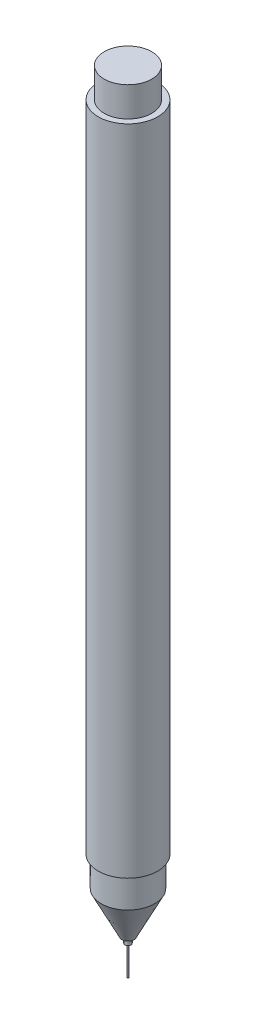
SolidWorks part; units mm, degrees
ref_plane "Front Plane" through (0, 0, 0) normal (0, 0, 1) x (1, 0, 0)
ref_plane "Top Plane" through (0, 0, 0) normal (0, 1, 0) x (1, 0, 0)
ref_plane "Right Plane" through (0, 0, 0) normal (1, 0, 0) x (0, 0, -1)
sketch "Sketch1" plane through (0, 0, 0) normal (0, 0, 1) x (1, 0, 0)
  line L0 (0, 75) -> (0, -75) construction
  line L1 (0, 75) -> (4, 75)
  line L2 (4, 75) -> (4, 70)
  line L3 (4, 70) -> (5, 70)
  line L4 (5, 70) -> (5, -40)
  line L5 (5, -40) -> (4.5, -40)
  line L6 (4.5, -40) -> (4.5, -45)
  line L7 (4.5, -45) -> (1.009, -52)
  line L8 (1.009, -52) -> (0.509, -52)
  line L9 (0.509, -52) -> (0.509, -53)
  line L10 (0.509, -53) -> (0.109, -53)
  line L11 (0.109, -53) -> (0.109, -58)
  line L12 (0.109, -58) -> (0, -58)
  line L13 (0, 75) -> (0, -58)
  point P4 (0, 0)
  point P17 (0, 0)
  dimension "D6" = 0.5
  dimension "D7" = 5
  dimension "D1" = 150
  dimension "D2" = 4
  dimension "D3" = 5
  dimension "D4" = 1
  dimension "D5" = 110
  dimension "D8" = 0.5
  dimension "D9" = 1
  dimension "D10" = 0.4
  dimension "D11" = 5
  dimension "D12" = 110
  dimension "D13" = 7
  dimension "D14" = 206.506
revolve "Revolve1" add sketch "Sketch1" angle 360 about L0
